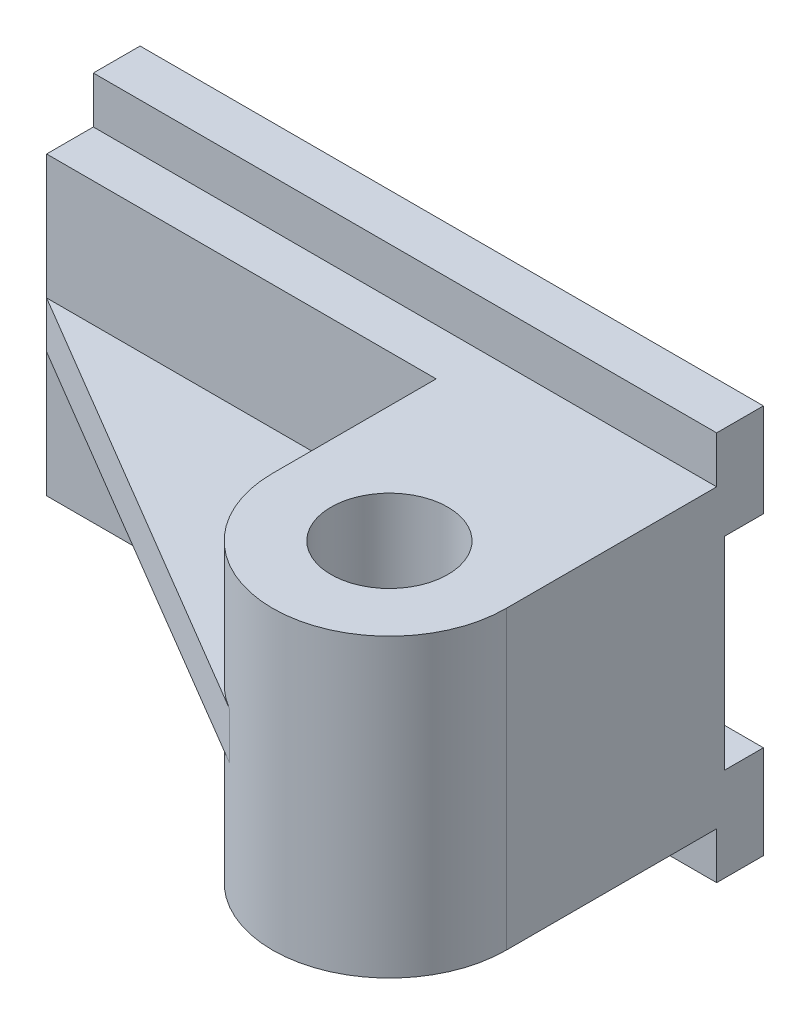
SolidWorks part; units mm, degrees
ref_plane "Front Plane" through (0, 0, 0) normal (0, 0, 1) x (1, 0, 0)
ref_plane "Top Plane" through (0, 0, 0) normal (0, 1, 0) x (1, 0, 0)
ref_plane "Right Plane" through (0, 0, 0) normal (1, 0, 0) x (0, 0, -1)
sketch "Sketch1" plane through (0, 0, 0) normal (0, 0, 1) x (1, 0, 0)
  line L1 (-80, -50) -> (80, -50)
  line L2 (-80, -50) -> (-80, 50)
  line L3 (-80, 50) -> (80, 50)
  line L4 (80, -50) -> (80, 50)
  line L5 (-80, -50) -> (80, 50) construction
  line L6 (-80, 50) -> (80, -50) construction
  point P0 (0, 0)
  dimension "D1" = 160
  dimension "D2" = 100
extrude "Boss-Extrude1" add sketch "Sketch1" against normal blind 12
sketch "Sketch2" plane through (0, 0, 0) normal (0, 0, 1) x (1, 0, 0)
  line L0 (-80, 50) -> (-80, -50) construction
  line L1 (-80, 38) -> (80, 38)
  line L2 (-80, 38) -> (-80, -38)
  line L3 (-80, -38) -> (80, -38)
  line L4 (80, 38) -> (80, -38)
  line L5 (80, -50) -> (80, 50) construction
  dimension "D1" = 76
extrude "Boss-Extrude2" add sketch "Sketch2" along normal blind 12
sketch "Sketch3" plane through (-80, 0, 0) normal (-1, 0, 0) x (0, 0, 1)
  line L0 (-12, 26) -> (-2, 26)
  line L1 (-12, 50) -> (-12, -50) construction
  line L2 (-2, 26) -> (-2, -26)
  line L3 (-2, -26) -> (-12, -26)
  dimension "D1" = 10
  dimension "D2" = 52
extrude "Cut-Extrude3" cut sketch "Sketch3" against normal through all both and the other way through all flip side to cut
sketch "Sketch5" plane through (0, -38, 0) normal (0, -1, 0) x (1, 0, 0)
  line L1 (80, 12) -> (20, 12)
  line L2 (80, 12) -> (80, 54)
  line L3 (80, 54) -> (20, 54)
  line L4 (20, 12) -> (20, 54)
  circle A0 centre (50, 54) radius 30
  line M5 (80, 12) -> (-80, 12)
  dimension "D1" = 60
  dimension "D2" = 42
extrude "Boss-Extrude3" add sketch "Sketch5" against normal blind 76 contours A0 L4 L2 M5 | L3 A0 | L3 A0
sketch "Sketch6" plane through (0, -38, 0) normal (0, -1, 0) x (1, 0, 0)
  circle A0 centre (50, 54) radius 15
  dimension "D1" = 30
extrude "Cut-Extrude4" cut sketch "Sketch6" against normal through all both and the other way through all
sketch "Sketch7" plane through (0, 0, 0) normal (0, 1, 0) x (1, 0, 0)
  line L0 (-80, -12) -> (34.7335, -79.825)
  arc A0 (20, -54) -> (80, -54) centre (50, -54) ccw construction
rib "Rib1" sketch "Sketch7" sketch "Sketch7" thickness 12 extrusion direction parallel to sketch draft on no parameters "D1"=12
